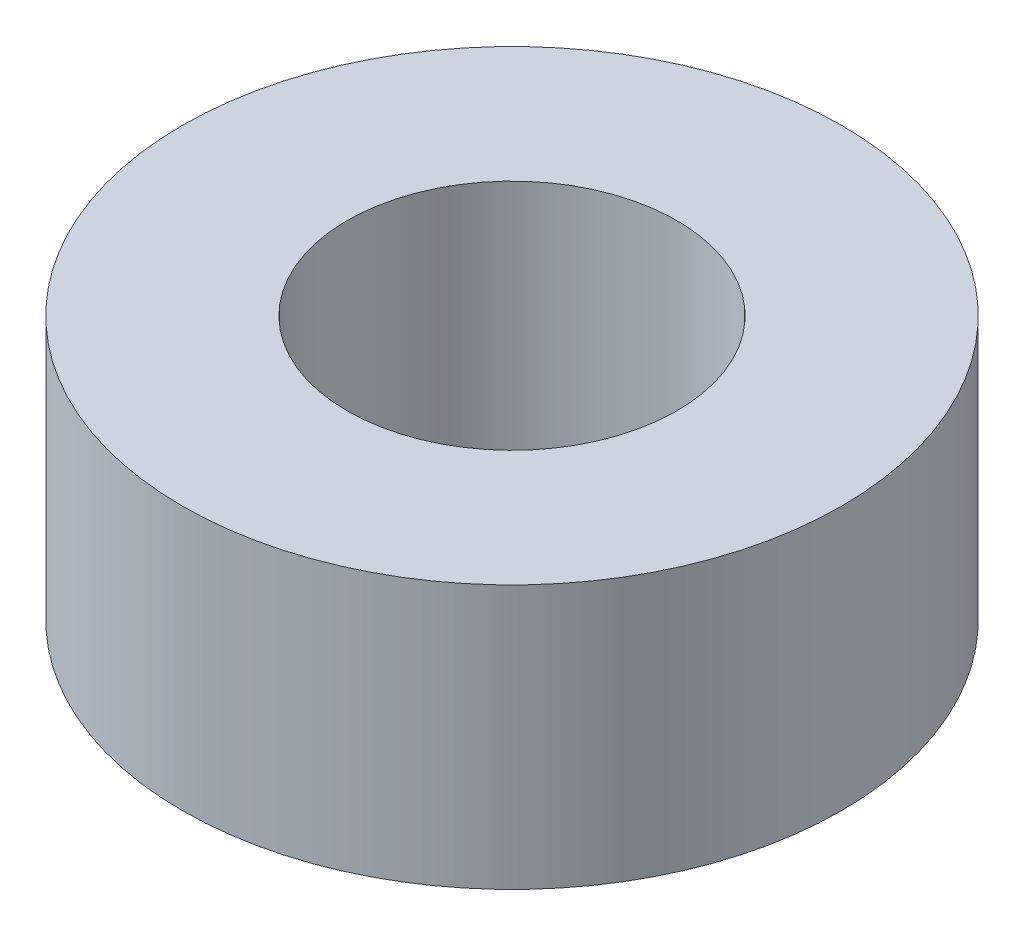
SolidWorks part; units mm, degrees
ref_plane "前视基准面" through (0, 0, 0) normal (0, 0, 1) x (1, 0, 0)
ref_plane "上视基准面" through (0, 0, 0) normal (0, 1, 0) x (1, 0, 0)
ref_plane "右视基准面" through (0, 0, 0) normal (1, 0, 0) x (0, 0, -1)
sketch "草图1" plane through (0, 0, 0) normal (0, 1, 0) x (1, 0, 0)
  circle A0 centre (0, 0) radius 5
  circle A1 centre (0, 0) radius 2.5
  dimension "D1" = 5
  dimension "D2" = 10
extrude "凸台-拉伸1" add sketch "草图1" along normal blind 4
